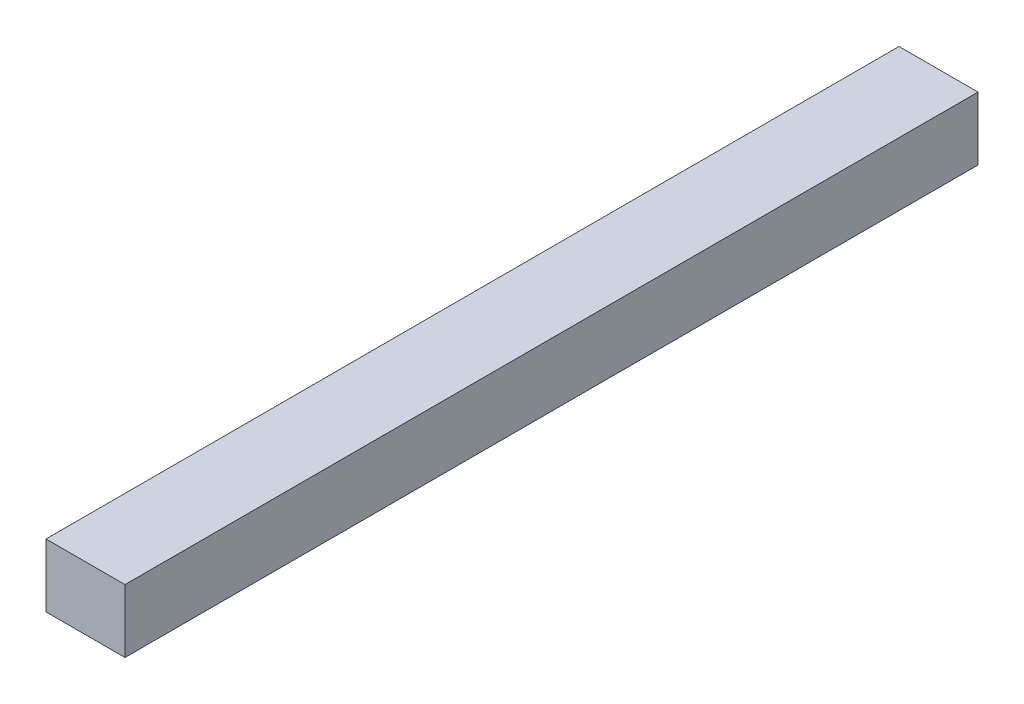
SolidWorks part; units mm, degrees
ref_plane "Plan de face" through (0, 0, 0) normal (0, 0, 1) x (1, 0, 0)
ref_plane "Plan de dessus" through (0, 0, 0) normal (0, 1, 0) x (1, 0, 0)
ref_plane "Plan de droite" through (0, 0, 0) normal (1, 0, 0) x (0, 0, -1)
sketch "Esquisse1" plane through (0, 0, 0) normal (0, 0, 1) x (1, 0, 0)
  line L1 (0, 0) -> (50, 0)
  line L2 (0, 0) -> (0, 40)
  line L3 (0, 40) -> (50, 40)
  line L4 (50, 0) -> (50, 40)
  dimension "D1" = 50
  dimension "D2" = 40
extrude "Boss.-Extru.1" add sketch "Esquisse1" along normal blind 540
